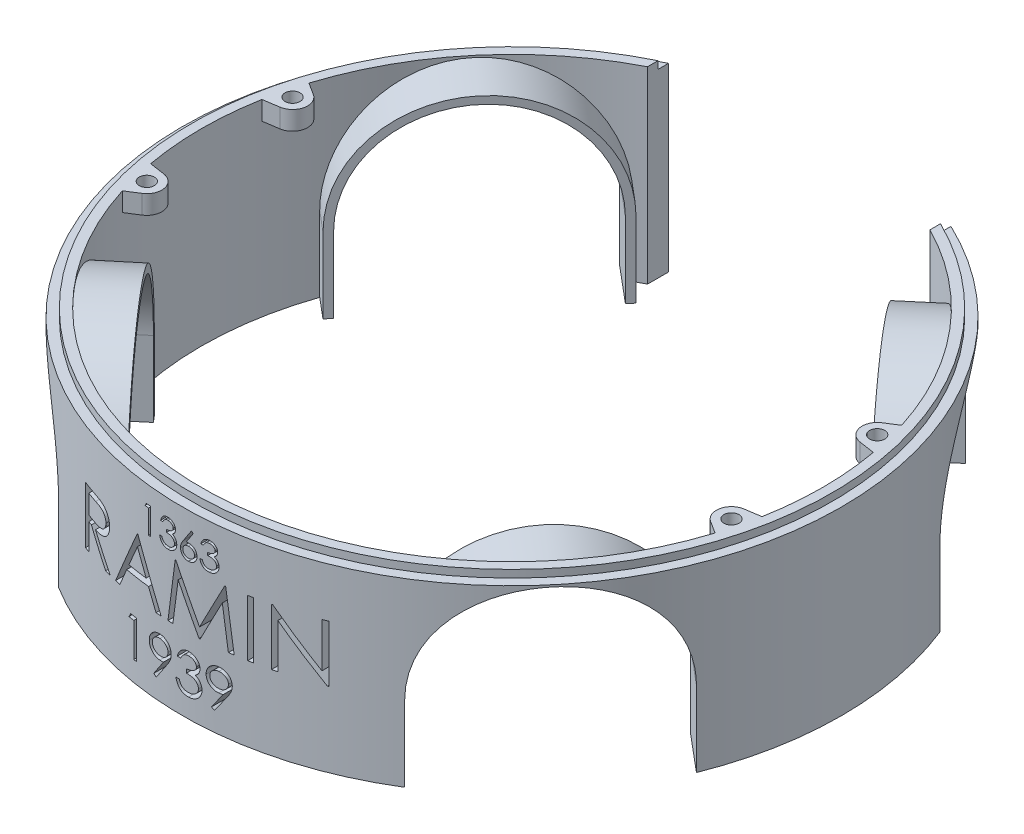
SolidWorks part; units mm, degrees
ref_plane "Front Plane" through (0, 0, 0) normal (0, 0, 1) x (1, 0, 0)
ref_plane "Top Plane" through (0, 0, 0) normal (0, 1, 0) x (1, 0, 0)
ref_plane "Right Plane" through (0, 0, 0) normal (1, 0, 0) x (0, 0, -1)
sketch "Sketch1" plane through (0, 0, 0) normal (0, 1, 0) x (1, 0, 0)
  circle A0 centre (0, 0) radius 87.5
  dimension "D1" = 175
extrude "Boss-Extrude1" add sketch "Sketch1" along normal blind 50
sketch "Sketch3" plane through (0, 50, 0) normal (0, 1, 0) x (1, 0, 0)
  line L0 (87.5, 0) -> (82.5, 0) construction
  circle A0 centre (0, 0) radius 87.5 construction
  circle A1 centre (0, 0) radius 82.5
  dimension "D1" = 5
extrude "Cut-Extrude1" cut sketch "Sketch3" against normal blind 50 contours A1
sketch "Sketch6" plane through (0, 50, 0) normal (0, 1, 0) x (1, 0, 0)
  line L0 (-37.5, 79.0569) -> (37.5, 79.0569) construction
  line L2 (-37.5, 119.3895) -> (37.5, 119.3895)
  line L3 (-37.5, 119.3895) -> (-37.5, 38.7244)
  line L4 (-37.5, 38.7244) -> (37.5, 38.7244)
  line L5 (37.5, 119.3895) -> (37.5, 38.7244)
  line L6 (-37.5, 119.3895) -> (37.5, 38.7244) construction
  line L7 (-37.5, 38.7244) -> (37.5, 119.3895) construction
  circle A1 centre (0, 0) radius 87.5 construction
  point P2 (0, 0)
  point P7 (0, 79.0569)
  circle M1 centre (0, 0) radius 82.5
  circle M2 centre (0, 0) radius 87.5
  dimension "D1" = 75
extrude "Cut-Extrude2" cut sketch "Sketch6" against normal blind 50 contours L0 M2 M1
sketch "Sketch7" plane through (0, 50, 0) normal (0, 1, 0) x (1, 0, 0)
  line L0 (-87.5, 0) -> (87.5, 0) construction
  line L1 (0, 0) -> (-77.6237, 19.3538) construction
  line L2 (-77.0229, 15.3991) -> (-81.1672, 14.7695)
  line L3 (-75.481, 22.7315) -> (-78.6938, 24.7695)
  line L5 (-77.6237, 21.3538) -> (-77.6237, 17.3538) construction
  circle A0 centre (-77.6237, 19.3538) radius 2
  arc A1 (-37.5, 79.0569) -> (37.5, 79.0569) centre (0, 0) ccw construction
  arc A2 (-77.0229, 15.3991) -> (-75.481, 22.7315) centre (-77.6237, 19.3538) ccw
  arc A3 (-37.5, 73.4847) -> (37.5, 73.4847) centre (0, 0) ccw construction
  arc A4 (-81.1672, 14.7695) -> (-78.6938, 24.7695) centre (0, 0) cw
  point P9 (-82.5, 0)
  point P16 (-82.3191, 5.4607)
  point P17 (-81.8752, 10.134)
  point P20 (-66.4381, 16.5649)
  point P22 (-74.5831, 35.2648)
  point P23 (-81.1672, 14.7695)
  dimension "D1" = 14
  dimension "D2" = 4
  dimension "D3" = 4
  dimension "D4" = 10
  dimension "D5" = 80
extrude "Boss-Extrude10" add sketch "Sketch7" against normal blind 5
mirror "Mirror1" about plane through (0, 0, 0) normal (1, 0, 0) of "Boss-Extrude10" second plane through (0, 0, 0) second plane normal (0, 0, 1)
sketch "Sketch8" plane through (0, 0, 0) normal (0, 0, 1) x (1, 0, 0)
  line L0 (0, 0) -> (0, 50) construction
  line L1 (-87.5, 0) -> (87.5, 0) construction
  line L2 (87.5, 50) -> (-87.5, 50) construction
ref_plane "Plane2" through (0, 0, 0) normal (0.766, 0, 0.6428) x (0, 1, 0)
sketch "Sketch9" plane through (0, 0, 0) normal (0.766, 0, 0.6428) x (0, 1, 0)
  line L0 (0, 0) -> (50, 0) construction
  line L1 (20, 27.5) -> (0, 27.5)
  line L2 (0, 82.5) -> (0, -82.5) construction
  line L3 (0, 27.5) -> (0, -27.5)
  line L4 (0, -27.5) -> (20, -27.5)
  arc A0 (20, -27.5) -> (20, 27.5) centre (20, 0) ccw
  dimension "D1" = 55
  dimension "D2" = 20
extrude "Cut-Extrude3" cut sketch "Sketch9" against normal through all
ref_plane "Plane3" through (-53.6231, 0, -44.9951) normal (0.766, 0, 0.6428) x (0, 1, 0)
sketch "Sketch10" plane through (-53.6231, 0, -44.9951) normal (0.766, 0, 0.6428) x (0, 1, 0)
  line L0 (20, -27.5) -> (0, -27.5) construction
  line L1 (0, 27.5) -> (20, 27.5) construction
  line L2 (20, -27.5) -> (0, -27.5)
  line L3 (0, 27.5) -> (20, 27.5)
  line L4 (0, 29.5) -> (20, 29.5)
  line L5 (20, -29.5) -> (0, -29.5)
  line L6 (0, 29.5) -> (0, 27.5)
  line L7 (0, -27.5) -> (0, -29.5)
  arc A0 (20, -27.5) -> (20, 27.5) centre (20, 0) ccw construction
  arc A1 (20, -27.5) -> (20, 27.5) centre (20, 0) ccw
  arc A2 (20, -29.5) -> (20, 29.5) centre (20, 0) ccw
  dimension "D1" = 2
extrude "Boss-Extrude11" add sketch "Sketch10" against normal up to next
mirror "Mirror2" about plane through (0, 0, 0) normal (0, 0, 1) of "Boss-Extrude11", "Cut-Extrude3" second plane through (0, 0, 0) second plane normal (1, 0, 0)
sketch "Sketch12" plane through (0, 50, 0) normal (0, 1, 0) x (1, 0, 0)
  line L0 (0, -87.5) -> (0, -82.5) construction
  arc A0 (-37.5, 79.0569) -> (37.5, 79.0569) centre (0, 0) ccw construction
  arc A1 (-78.6938, -24.7695) -> (78.6938, -24.7695) centre (0, 0) ccw construction
sketch "Sketch13" plane through (0, 50, 0) normal (0, 1, 0) x (1, 0, 0)
  circle A0 centre (0, 0) radius 85
  circle A1 centre (0, 0) radius 87.5
  arc A2 (-37.5, 79.0569) -> (37.5, 79.0569) centre (0, 0) ccw construction
  dimension "D1" = 2.5
extrude "Cut-Extrude4" cut sketch "Sketch13" against normal blind 2
sketch "Sketch16" plane through (0, 0, 0) normal (0, 0, 1) x (1, 0, 0)
  text T0 "RAMIN\r\n" font "Century Gothic" height 15
  text T1 "1363\r\n" font "Century Gothic" height 7
  text T2 "1939" font "Century Gothic" height 10
extrude "Cut-Extrude9" cut sketch "Sketch16" along normal blind 10000
